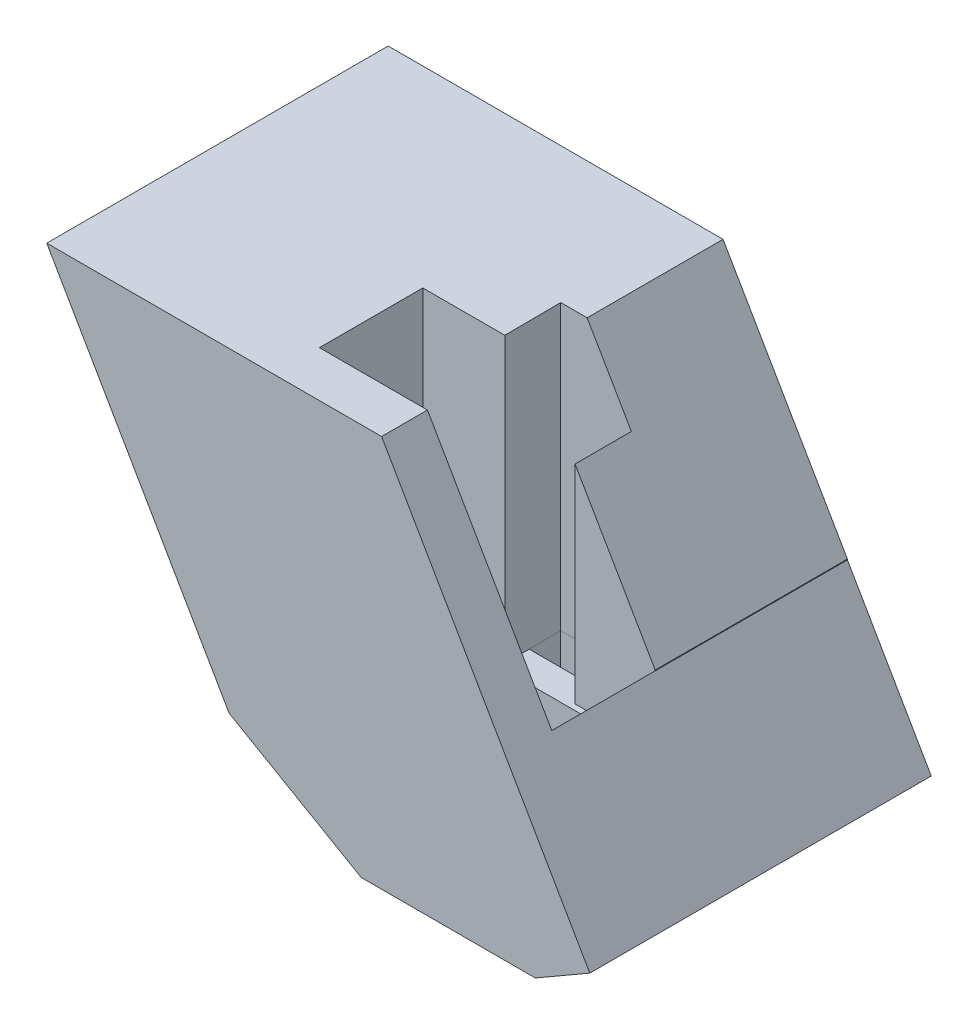
SolidWorks part; units mm, degrees
material "ABS"
ref_plane "前基準面" through (0, 0, 0) normal (0, 0, 1) x (1, 0, 0)
ref_plane "上基準面" through (0, 0, 0) normal (0, 1, 0) x (1, 0, 0)
ref_plane "右基準面" through (0, 0, 0) normal (1, 0, 0) x (0, 0, -1)
sketch "草圖1" plane through (0, 0, 0) normal (0, 0, 1) x (1, 0, 0)
  line L0 (35.0077, 40.3722) -> (51.8511, 50.0967)
  line L1 (51.8511, 50.0967) -> (80.6555, 33.4665)
  line L2 (80.6555, 33.4665) -> (80.6555, 14.0174)
  line L3 (80.6555, 14.0174) -> (35.0077, 40.3722)
  line L4 (45.0077, 46.1457) -> (80.6555, 25.5645)
  line L5 (80.6555, 33.4665) -> (120.6555, 33.4665)
  line L6 (120.6555, 33.4665) -> (120.1555, 34.3326)
  line L7 (120.1555, 34.3326) -> (130.5478, 40.3326)
  line L8 (130.5478, 40.3326) -> (130.5478, 33.4665)
  line L9 (130.5478, 33.4665) -> (120.6555, 33.4665)
  line L10 (51.8511, 50.0967) -> (12.0561, 119.0237)
  line L11 (12.0561, 119.0237) -> (85.1154, 119.0237)
  line L12 (85.1154, 119.0237) -> (130.5478, 40.3326)
  circle A0 centre (46.7546, 39.3636) radius 2.1
  circle A1 centre (64.0751, 29.3636) radius 2.1
  dimension "D1" = 4.2
  dimension "D2" = 4.2
  dimension "D4" = 5
  dimension "D5" = 5
  dimension "D6" = 20
  dimension "D7" = 15.3462
  dimension "D8" = 11.7469
  dimension "D3" = 90
  dimension "D9" = 10
  dimension "D10" = 60
  dimension "D11" = 60
  dimension "D12" = 40
  dimension "D13" = 1
  dimension "D14" = 90
  dimension "D15" = 60
  dimension "D16" = 79.59
  dimension "D17" = 12
  dimension "D18" = 60
  dimension "D19" = 90
extrude "填料-伸長1" add sketch "草圖1" along normal blind 10 contours L12 L11 L10 L1 L5 L6 L7 | L0 L4 L2 L1
sketch "草圖2" plane through (0, 0, 0) normal (0, 0, -1) x (-1, 0, 0)
  line L0 (-80.6555, 25.5645) -> (-80.6555, 33.4665)
  line L1 (-80.6555, 33.4665) -> (-120.6555, 33.4665)
  line L2 (-120.6555, 33.4665) -> (-120.1555, 34.3326)
  line L3 (-120.1555, 34.3326) -> (-130.5478, 40.3326)
  line L4 (-130.5478, 40.3326) -> (-85.1154, 119.0237)
  line L5 (-85.1154, 119.0237) -> (-12.0561, 119.0237)
  line L6 (-12.0561, 119.0237) -> (-51.8511, 50.0967)
  line L7 (-51.8511, 50.0967) -> (-45.0077, 46.1457)
  line L8 (-45.0077, 46.1457) -> (-80.6555, 25.5645)
  line L9 (-61.5528, 119.0237) -> (-61.5528, 57.0205)
  line L10 (-61.5528, 57.0205) -> (-112.2528, 57.0205)
  line L11 (-112.2528, 57.0205) -> (-112.2528, 72.0205)
  line M4 (-130.5478, 40.3326) -> (-120.1555, 34.3326)
  line M5 (-120.1555, 34.3326) -> (-120.6555, 33.4665)
  line M6 (-120.6555, 33.4665) -> (-80.6555, 33.4665)
  line M7 (-80.6555, 33.4665) -> (-80.6555, 25.5645)
  line M8 (-80.6555, 25.5645) -> (-45.0077, 46.1457)
  line M9 (-45.0077, 46.1457) -> (-51.8511, 50.0967)
  line M10 (-51.8511, 50.0967) -> (-12.0561, 119.0237)
  line M11 (-12.0561, 119.0237) -> (-85.1154, 119.0237)
  dimension "D1" = 50.7
  dimension "D2" = 15
  dimension "D3" = 23.5627
extrude "填料-伸長2" add sketch "草圖2" along normal up to surface (64.5 mm away) contours L10 L11 L4 L9 M4 M5 M6 M7 M8 M9 M10 M11
sketch "草圖4" plane through (0, 57.0205, 0) normal (0, 1, 0) x (1, 0, 0)
  line L0 (112.2528, 64.5) -> (112.2528, 0) construction
  line L1 (64.0528, 0) -> (109.7528, 0)
  line L2 (64.0528, 0) -> (64.0528, 21.3)
  line L3 (64.0528, 21.3) -> (109.7528, 21.3)
  line L4 (109.7528, 0) -> (109.7528, 21.3)
  line L5 (61.5528, 64.5) -> (61.5528, 0) construction
  dimension "D1" = 21.3
  dimension "D2" = 2.5
  dimension "D3" = 2.5
  dimension "D4" = 45.7
extrude "除料-伸長1" cut sketch "草圖4" against normal up to next
sketch "草圖5" plane through (0, 57.0205, 0) normal (0, 1, 0) x (1, 0, 0)
  line L1 (64.0528, 0) -> (70.0528, 0)
  line L2 (64.0528, 0) -> (64.0528, 6)
  line L3 (64.0528, 6) -> (70.0528, 6)
  line L4 (70.0528, 0) -> (70.0528, 6)
  line L5 (109.7528, 21.3) -> (103.7528, 21.3)
  line L6 (109.7528, 21.3) -> (109.7528, 15.3)
  line L7 (109.7528, 15.3) -> (103.7528, 15.3)
  line L8 (103.7528, 21.3) -> (103.7528, 15.3)
  circle A2 centre (66.5528, 2.5) radius 1.4
  circle A3 centre (107.2528, 18.8) radius 1.3
  circle A4 centre (105.2528, 16.8) radius 1.5
  circle A5 centre (68.5528, 4.5) radius 1.5
  line M10 (64.0528, 0) -> (64.0528, 21.3)
  line M11 (64.0528, 21.3) -> (109.7528, 21.3)
  line M12 (109.7528, 21.3) -> (109.7528, 0)
  dimension "D1" = 6
  dimension "D2" = 6
  dimension "D5" = 2.5
  dimension "D6" = 2.5
  dimension "D7" = 2.8
  dimension "D8" = 2.5
  dimension "D9" = 2.5
  dimension "D10" = 1.5
  dimension "D11" = 1.5
  dimension "D12" = 3
  dimension "D13" = 1.5
  dimension "D14" = 1.5
  dimension "D15" = 3
  dimension "D16" = 2.6
  dimension "D3" = 6
  dimension "D4" = 6
extrude "填料-伸長4" add sketch "草圖5" along direction (0, 1, 0) on the side against the normal blind 3 contours A2 A5 | A5 A2 L3 L1 L4 M10 | A4 A3 | A4 L7 L8 A3 M12 M11
sketch "草圖6" plane through (0, 57.0205, 0) normal (0, 1, 0) x (1, 0, 0)
  line L1 (79.3526, 34.8525) -> (94.763, 34.8525)
  line L2 (79.3526, 34.8525) -> (79.3526, 27.9116)
  line L3 (79.3526, 27.9116) -> (94.763, 27.9116)
  line L4 (94.763, 34.8525) -> (94.763, 27.9116)
extrude "除料-伸長2" cut sketch "草圖6" against normal up to next
sketch "草圖7" plane through (0, 57.0205, 0) normal (0, 1, 0) x (1, 0, 0)
  line L0 (94.763, 34.8532) -> (94.763, 22.5635)
  line L1 (94.763, 22.5635) -> (112.2528, 22.5635)
  line L2 (112.2528, 64.5) -> (112.2528, 0) construction
  line L3 (112.2528, 22.5635) -> (112.2528, 64.5)
  line L4 (112.2528, 64.5) -> (61.5528, 64.5) construction
  line L5 (112.2528, 64.5) -> (61.5528, 64.5)
  line L6 (61.5528, 64.5) -> (61.5528, 22.5635)
  line L7 (61.5528, 64.5) -> (61.5528, 0) construction
  line L8 (61.5528, 22.5635) -> (79.4383, 22.5635)
  line L9 (79.4383, 22.5635) -> (79.3526, 34.8525)
  line L11 (79.3526, 34.8525) -> (94.763, 34.8532)
  line L14 (79.3526, 34.8525) -> (79.3526, 27.9116) construction
  line L15 (94.763, 34.8525) -> (79.3526, 34.8525) construction
extrude "填料-伸長7" add sketch "草圖7" along normal up to surface (62.0032 mm away) up to face at (52.9081, 119.0237, -18.1667)
sketch "草圖9" plane through (0, 0, 10) normal (0, 0, 1) x (1, 0, 0)
  line L0 (85.1154, 119.0237) -> (125.8573, 119.0237)
  line L1 (125.8573, 119.0237) -> (125.8573, 48.6886)
  line L2 (125.8573, 48.6886) -> (85.1154, 119.0237)
extrude "除料-伸長3" cut sketch "草圖9" against normal up to surface (74.5 mm away) up to face at (86.609, 57.3473, -64.5)
sketch "草圖10" plane through (0, 0, -64.5) normal (0, 0, -1) x (-1, 0, 0)
  line L0 (-120.1555, 34.3326) -> (-118.6555, 33.4665)
  line L1 (-80.6555, 33.4665) -> (-120.6555, 33.4665) construction
  line L2 (-118.6555, 33.4665) -> (-120.6555, 33.4665)
  line L3 (-120.6555, 33.4665) -> (-120.1555, 34.3326)
extrude "除料-伸長4" cut sketch "草圖10" against normal up to next
sketch "草圖11" plane through (0, 0, -64.5) normal (0, 0, -1) x (-1, 0, 0)
  line L0 (-45.0077, 46.1457) -> (-80.6555, 25.5645)
  line L1 (-80.6555, 25.5645) -> (-80.6555, 33.4665)
  line L2 (-80.6555, 33.4665) -> (-51.8511, 50.0967)
  line L3 (-51.8511, 50.0967) -> (-45.0077, 46.1457)
extrude "除料-伸長5" cut sketch "草圖11" against normal up to next
